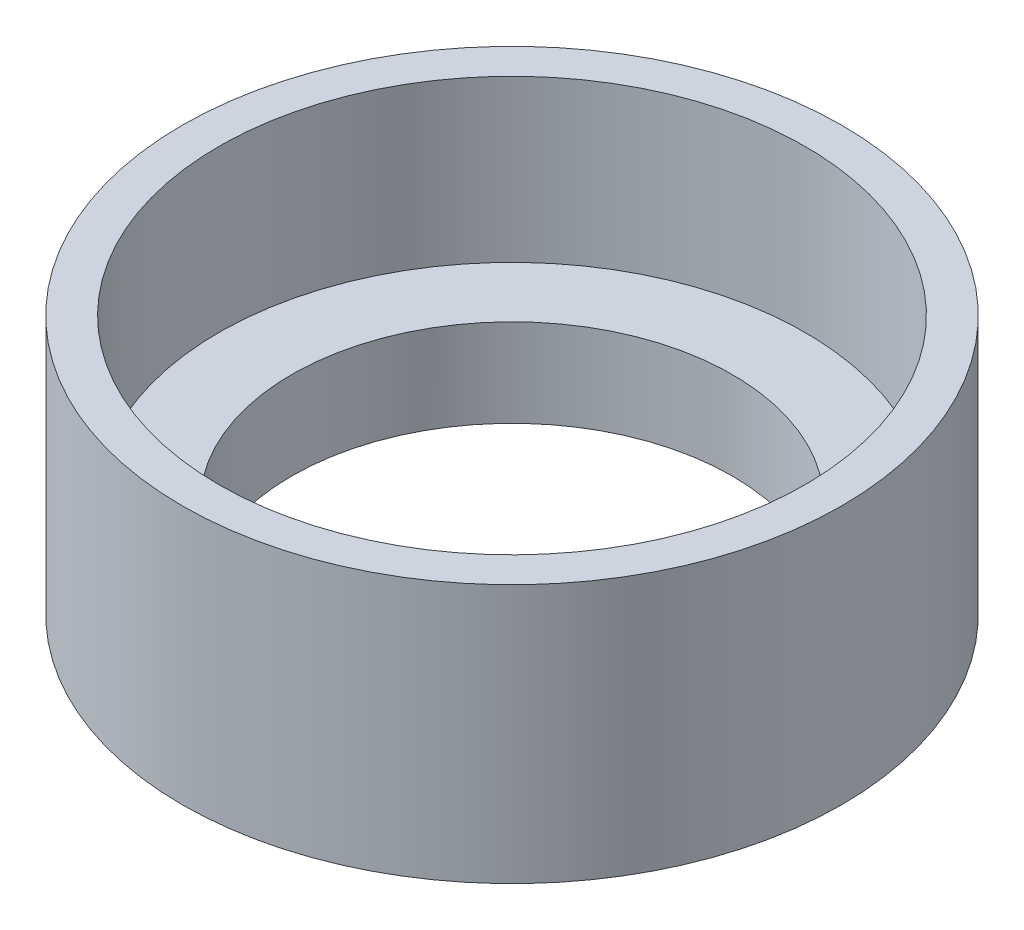
SolidWorks part; units mm, degrees
material "PLA"
ref_plane "Front Plane" through (0, 0, 0) normal (0, 0, 1) x (1, 0, 0)
ref_plane "Top Plane" through (0, 0, 0) normal (0, 1, 0) x (1, 0, 0)
ref_plane "Right Plane" through (0, 0, 0) normal (1, 0, 0) x (0, 0, -1)
sketch "Sketch1" plane through (0, 0, 0) normal (0, 1, 0) x (1, 0, 0)
  circle A0 centre (0, 0) radius 75
  circle A1 centre (0, 0) radius 62.3
  dimension "D1" = 150
  dimension "D2" = 124.6
extrude "Boss-Extrude1" add sketch "Sketch1" along normal blind 53
sketch "Sketch2" plane through (0, 0, 0) normal (0, -1, 0) x (1, 0, 0)
  circle A0 centre (0, 0) radius 75
  circle A1 centre (0, 0) radius 48
  dimension "D1" = 96
ref_plane "Plane1" through (0, 20, 0) normal (0, -1, 0) x (-1, 0, 0)
sketch "Sketch3" plane through (0, 20, 0) normal (0, -1, 0) x (-1, 0, 0)
  circle A0 centre (0, 0) radius 75
  circle A1 centre (0, 0) radius 47
  dimension "96" = 94
extrude "Boss-Extrude3" add sketch "Sketch3" along normal blind 3
sketch "Sketch4" plane through (0, 17, 0) normal (0, -1, 0) x (1, 0, 0)
  circle A0 centre (0, 0) radius 50.1
  circle A1 centre (0, 0) radius 47
  dimension "D1" = 100.2
extrude "Boss-Extrude4" add sketch "Sketch4" along normal blind 14
sketch "Sketch5" plane through (0, 17, 0) normal (0, -1, 0) x (1, 0, 0)
  circle A0 centre (0, 0) radius 62.3
  circle A1 centre (0, 0) radius 50.1
extrude "Boss-Extrude5" add sketch "Sketch5" along normal blind 1
sketch "Sketch6" plane through (0, 53, 0) normal (0, 1, 0) x (1, 0, 0)
  circle A2 centre (0, 0) radius 67.5
  circle A3 centre (0, 0) radius 75
  dimension "D1" = 135
extrude "Cut-Extrude2" cut sketch "Sketch6" against normal blind 64
sketch "Sketch7" plane through (0, 53, 0) normal (0, 1, 0) x (1, 0, 0)
  circle A0 centre (0, 0) radius 60
  circle A1 centre (0, 0) radius 62.3
  dimension "D1" = 120
extrude "Boss-Extrude6" add sketch "Sketch7" against normal up to surface (53 mm away) up to face at (0, 0, 62.3)
sketch "Sketch9" plane through (0, 3, 0) normal (0, -1, 0) x (1, 0, 0)
  circle A0 centre (0, 0) radius 50.1
  circle A1 centre (0, 0) radius 47
extrude "Cut-Extrude3" cut sketch "Sketch9" against normal up to surface (17 mm away) up to face at (0, 20, -47)
sketch "Sketch10" plane through (0, 20, 0) normal (0, 1, 0) x (1, 0, 0)
  circle A0 centre (0, 0) radius 50.1
  circle A1 centre (0, 0) radius 48.5
  dimension "D1" = 97
extrude "Boss-Extrude7" add sketch "Sketch10" against normal up to surface (4 mm away) up to face at (0, 16, -50.1)
sketch "Sketch11" plane through (0, 16, 0) normal (0, -1, 0) x (1, 0, 0)
  circle A0 centre (0, 0) radius 47.6
  circle A1 centre (0, 0) radius 45.1
  dimension "D1" = 95.2
  dimension "D2" = 90.2
sketch "Sketch12" plane through (0, 16, 0) normal (0, -1, 0) x (1, 0, 0)
  circle A0 centre (0, 0) radius 47.6
  circle A1 centre (0, 0) radius 48.5
extrude "Boss-Extrude8" add sketch "Sketch12" against normal up to surface (4 mm away) up to face at (0, 20, -60)
sketch "Sketch13" plane through (0, 20, 0) normal (0, 1, 0) x (1, 0, 0)
  circle A0 centre (0, 0) radius 45.1
  circle A1 centre (0, 0) radius 47.6
extrude "Boss-Extrude9" add sketch "Sketch13" against normal blind 17
sketch "Sketch14" plane through (0, 3, 0) normal (0, -1, 0) x (1, 0, 0)
  circle A0 centre (0, 0) radius 47.65
  circle A1 centre (0, 0) radius 47.6
  dimension "D1" = 95.3
  dimension "D2" = 95.2
extrude "Boss-Extrude10" add sketch "Sketch14" against normal up to surface (13 mm away) up to face at (0, 16, -60)
sketch "Sketch15" plane through (0, 3, 0) normal (0, -1, 0) x (1, 0, 0)
  circle A0 centre (0, 0) radius 45.1 construction
  circle A1 centre (0, 0) radius 45.1
  circle A2 centre (0, 0) radius 47.65 construction
  circle A3 centre (0, 0) radius 47.65
extrude "Boss-Extrude11" add sketch "Sketch15" along normal blind 1
